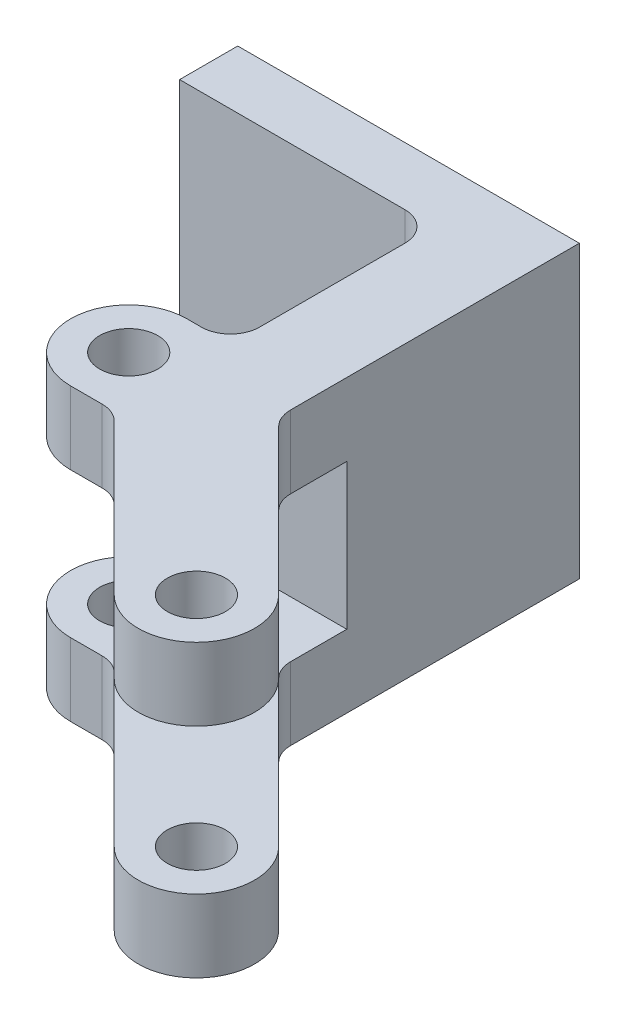
SolidWorks part; units mm, degrees
material "ABS"
ref_plane "Front Plane" through (0, 0, 0) normal (0, 0, 1) x (1, 0, 0)
ref_plane "Top Plane" through (0, 0, 0) normal (0, 1, 0) x (1, 0, 0)
ref_plane "Right Plane" through (0, 0, 0) normal (1, 0, 0) x (0, 0, -1)
sketch "Sketch1" plane through (0, 0, 0) normal (0, 1, 0) x (1, 0, 0)
  line L0 (0, -4) -> (0, 18)
  line L1 (0, 18) -> (-17.5, 18)
  line L2 (-17.5, 18) -> (-17.5, 22)
  line L3 (-17.5, 22) -> (6, 22)
  line L4 (6, 22) -> (6, -4)
  line L5 (0, -4) -> (6, -4)
  dimension "D1" = 4
  dimension "D2" = 4
  dimension "D3" = 6
  dimension "D5" = 26
  dimension "13.5" = 17.5
extrude "Boss-Extrude1" add sketch "Sketch1" along normal mid plane 20
sketch "Sketch3" plane through (0, 0, 0) normal (0, 1, 0) x (1, 0, 0)
  line L1 (-3, 4) -> (0, 4)
  line L2 (0, 4) -> (0, -4)
  line L3 (0, -4) -> (-3, -4)
  line L4 (0, 18) -> (0, -4) construction
  circle A0 centre (-3, 0) radius 2
  arc A1 (-3, 4) -> (-3, -4) centre (-3, 0) ccw
  dimension "D1" = 4
  dimension "D2" = 8
  dimension "D3" = 3
extrude "Boss-Extrude2" add sketch "Sketch3" along normal mid plane 20
sketch "Sketch5" plane through (0, 10, 0) normal (0, 1, 0) x (1, 0, 0)
  line L0 (0, -4) -> (10.9497, -14.9497)
  line L1 (16.6066, -9.2929) -> (10.9497, -14.9497) construction
  line L2 (16.6066, -9.2929) -> (6, 1.3137)
  line L3 (6, -4) -> (6, 22) construction
  line L4 (0, -4) -> (6, 1.3137)
  line L5 (-3, -4) -> (6, -4) construction
  line L6 (-3, -4) -> (6, -4) construction
  arc A0 (10.9497, -14.9497) -> (16.6066, -9.2929) centre (13.7782, -12.1213) ccw
  dimension "D1" = 4
  dimension "D2" = 45
  dimension "D3" = 15
extrude "Boss-Extrude3" add sketch "Sketch5" against normal up to surface (20 mm away) up to face at (-4.125, -10, -10)
sketch "Sketch6" plane through (0, 10, 0) normal (0, 1, 0) x (1, 0, 0)
  line L1 (16.6066, -9.2929) -> (10.9497, -14.9497) construction
  line L2 (16.6066, -9.2929) -> (6, 1.3137) construction
  line L3 (0, -4) -> (10.9497, -14.9497) construction
  line L4 (16.6066, -9.2929) -> (6, 1.3137) construction
  circle A0 centre (13.7782, -12.1213) radius 2
  arc A1 (10.9497, -14.9497) -> (16.6066, -9.2929) centre (13.7782, -12.1213) ccw construction
  dimension "D1" = 4
extrude "Cut-Extrude2" cut sketch "Sketch6" against normal up to surface (20 mm away) up to face at (-0.2377, -10, -4.9311)
ref_plane "Plane1" through (0, 0, -6) normal (0, 0, -1) x (-1, 0, 0)
sketch "Sketch4" plane through (0, 0, -6) normal (0, 0, 1) x (1, 0, 0)
  line L1 (22.5, 5) -> (-17.5, 5)
  line L2 (22.5, 5) -> (22.5, -5)
  line L3 (22.5, -5) -> (-17.5, -5)
  line L4 (-17.5, 5) -> (-17.5, -5)
  line L7 (-17.5, 10) -> (-17.5, -10) construction
  line L8 (0, 10) -> (0, -10) construction
  point P6 (0, 0)
  point P7 (-17.5, 0)
  dimension "D1" = 10
  dimension "D2" = 40
extrude "Cut-Extrude1" cut sketch "Sketch4" along normal through all
fillet "Fillet1" radius 2 7 edges at (6, 7.5, -1.3137) (6, -7.5, -1.3137) (0, -7.5, 4) (0, 7.5, 4) (0, 0, -18) (0, -7.5, -4) (0, 7.5, -4)
